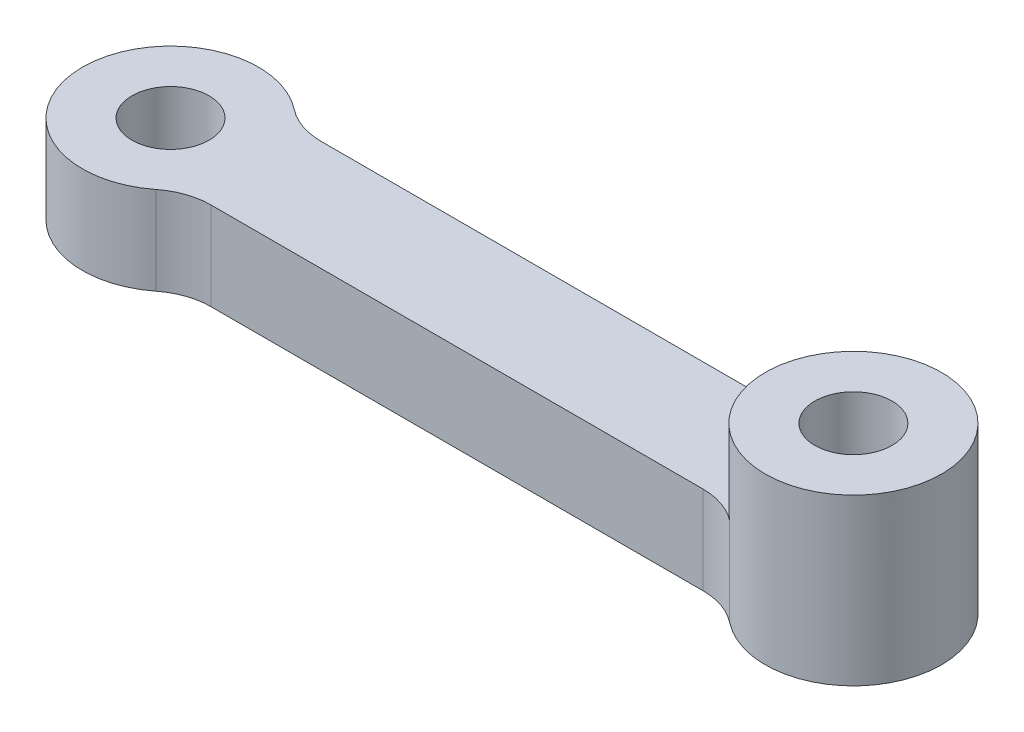
SolidWorks part; units mm, degrees
ref_plane "Front Plane" through (0, 0, 0) normal (0, 0, 1) x (1, 0, 0)
ref_plane "Top Plane" through (0, 0, 0) normal (0, 1, 0) x (1, 0, 0)
ref_plane "Right Plane" through (0, 0, 0) normal (1, 0, 0) x (0, 0, -1)
ref_plane "Plane1" through (0, 0, 0) normal (0, -1, 0) x (1, 0, 0)
sketch "Sketch1" plane through (0, 0, 0) normal (0, -1, 0) x (1, 0, 0)
  line L0 (26.6699, 2.5) -> (4.3301, 2.5)
  line L1 (4.3301, -2.5) -> (26.6699, -2.5)
  circle A0 centre (31, 0) radius 1.75
  circle A1 centre (0, 0) radius 1.75
  arc A2 (28.5256, 3.1429) -> (26.6699, 2.5) centre (26.6699, 5.5) cw
  arc A3 (4.3301, 2.5) -> (2.4744, 3.1429) centre (4.3301, 5.5) cw
  arc A4 (2.4744, 3.1429) -> (2.4744, -3.1429) centre (0, 0) ccw
  arc A5 (2.4744, -3.1429) -> (4.3301, -2.5) centre (4.3301, -5.5) cw
  arc A6 (26.6699, -2.5) -> (28.5256, -3.1429) centre (26.6699, -5.5) cw
  arc A7 (28.5256, -3.1429) -> (28.5256, 3.1429) centre (31, 0) ccw
extrude "Boss-Extrude1" add sketch "Sketch1" against normal blind 4
sketch "Sketch2" plane through (0, 4, 0) normal (0, 1, 0) x (1, 0, 0)
  circle A0 centre (31, 0) radius 1.75
  circle A1 centre (31, 0) radius 4
extrude "Boss-Extrude2" add sketch "Sketch2" along normal blind 3.5
